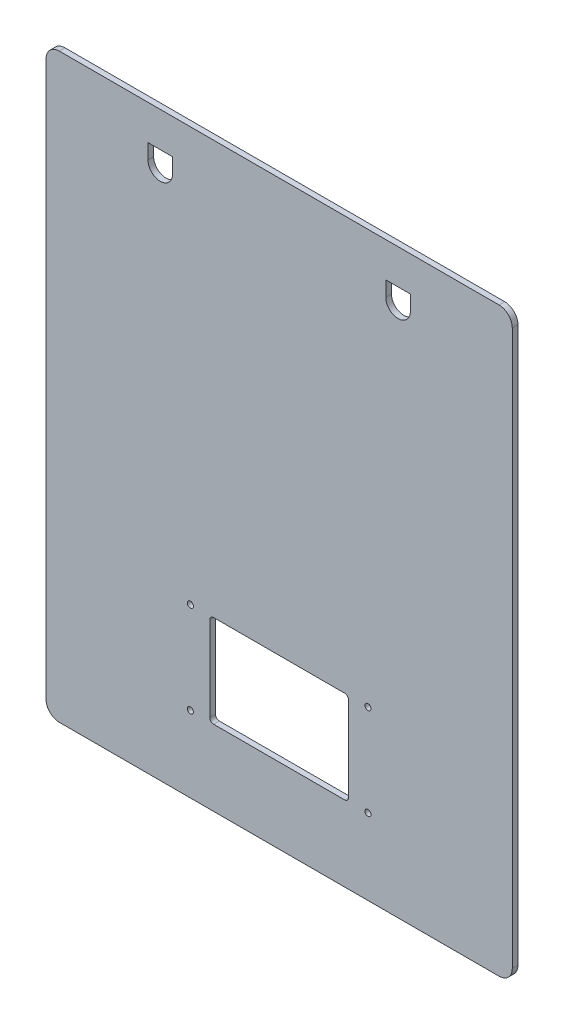
SolidWorks part; units mm, degrees
ref_plane "Plan de face" through (0, 0, 0) normal (0, 0, 1) x (1, 0, 0)
ref_plane "Plan de dessus" through (0, 0, 0) normal (0, 1, 0) x (1, 0, 0)
ref_plane "Plan de droite" through (0, 0, 0) normal (1, 0, 0) x (0, 0, -1)
sketch "Esquisse1" plane through (0, 0, 0) normal (0, 0, 1) x (1, 0, 0)
  line L1 (7, 0) -> (240, 0)
  line L2 (0, 7) -> (0, 301)
  line L3 (7, 308) -> (240, 308)
  line L4 (247, 7) -> (247, 301)
  arc A0 (0, 7) -> (7, 0) centre (7, 7) ccw
  arc A1 (240, 0) -> (247, 7) centre (240, 7) ccw
  arc A2 (247, 301) -> (240, 308) centre (240, 301) ccw
  arc A3 (0, 301) -> (7, 308) centre (7, 301) cw
  point P7 (0, 0)
  point P10 (247, 0)
  point P15 (0, 308)
  dimension "D3" = 7
  dimension "D1" = 247
  dimension "D2" = 308
extrude "Boss.-Extru.1" add sketch "Esquisse1" along normal blind 3
sketch "Esquisse2" plane through (0, 0, 0) normal (0, 0, -1) x (-1, 0, 0)
  line L0 (-54, 289.5) -> (-67, 289.5)
  line L2 (-54, 289.5) -> (-54, 281.5) construction
  line L3 (-67, 281.5) -> (-67, 289.5) construction
  line L6 (-193, 281.5) -> (-193, 289.5) construction
  line L7 (-180, 289.5) -> (-180, 281.5) construction
  line L11 (-67, 289.5) -> (-67, 281.5)
  line L12 (-54, 289.5) -> (-54, 281.5)
  line L13 (-123.5, 308) -> (-123.5, 169.7769) construction
  line L14 (-240, 308) -> (-7, 308) construction
  line L15 (-180, 281.5) -> (-180, 289.5) construction
  line L16 (-193, 289.5) -> (-193, 281.5) construction
  line L17 (-193, 289.5) -> (-193, 281.5)
  line L18 (-180, 289.5) -> (-180, 281.5)
  line L19 (-180, 289.5263) -> (-180, 289.5)
  line L20 (-193, 289.5263) -> (-180, 289.5263)
  line L21 (-193, 289.5) -> (-193, 289.5263)
  arc A1 (-67, 281.5) -> (-54, 281.5) centre (-60.5, 281.5) ccw construction
  arc A3 (-193, 281.5) -> (-180, 281.5) centre (-186.5, 281.5) ccw construction
  arc A4 (-54, 281.5) -> (-67, 281.5) centre (-60.5, 281.5) cw
  arc A5 (-180, 281.5) -> (-193, 281.5) centre (-186.5, 281.5) cw construction
  arc A6 (-193, 281.5) -> (-180, 281.5) centre (-186.5, 281.5) ccw
extrude "Enlèv. mat.-Extru.1" cut sketch "Esquisse2" against normal through all
sketch "Esquisse3" plane through (0, 0, 0) normal (0, 0, -1) x (-1, 0, 0)
  line L0 (-158.22, 88.96) -> (-88.78, 88.96)
  line L1 (-160.22, 86.96) -> (-160.22, 42)
  line L2 (-158.22, 40) -> (-88.78, 40)
  line L3 (-86.78, 86.96) -> (-86.78, 42)
  line L4 (-123.5, 0) -> (-123.5, 233.0402) construction
  line L5 (-7, 0) -> (-240, 0) construction
  line L6 (-160.22, 64.48) -> (-230.8465, 64.48) construction
  arc A0 (-88.78, 88.96) -> (-86.78, 86.96) centre (-88.78, 86.96) cw
  arc A1 (-86.78, 42) -> (-88.78, 40) centre (-88.78, 42) cw
  arc A2 (-158.22, 40) -> (-160.22, 42) centre (-158.22, 42) cw
  arc A3 (-158.22, 88.96) -> (-160.22, 86.96) centre (-158.22, 86.96) ccw
  circle A4 centre (-170.55, 88.75) radius 1.6
  circle A5 centre (-76.45, 40.21) radius 1.6
  circle A6 centre (-170.55, 40.21) radius 1.6
  circle A7 centre (-76.45, 88.75) radius 1.6
  point P18 (-123.5, 40)
  point P29 (0, 0)
  dimension "D1" = 2
  dimension "D4" = 3.2
  dimension "D5" = 40
  dimension "D6" = 3.2
  dimension "D2" = 73.44
  dimension "D3" = 44.96
  dimension "D8" = 24.27
  dimension "D9" = 24.27
  dimension "D10" = 47.05
  dimension "D11" = 47.05
extrude "Enlèv. mat.-Extru.2" cut sketch "Esquisse3" against normal through all
